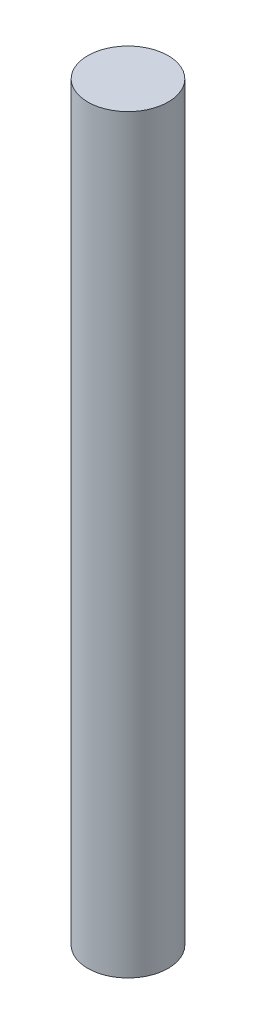
SolidWorks part; units mm, degrees
material "AISI 1020"
ref_plane "Front Plane" through (0, 0, 0) normal (0, 0, 1) x (1, 0, 0)
ref_plane "Top Plane" through (0, 0, 0) normal (0, 1, 0) x (1, 0, 0)
ref_plane "Right Plane" through (0, 0, 0) normal (1, 0, 0) x (0, 0, -1)
sketch "Sketch1" plane through (0, 0, 0) normal (0, 1, 0) x (1, 0, 0)
  circle A0 centre (0, 0) radius 9.525
  dimension "D1" = 19.05
extrude "Boss-Extrude1" add sketch "Sketch1" along normal blind 177.8
